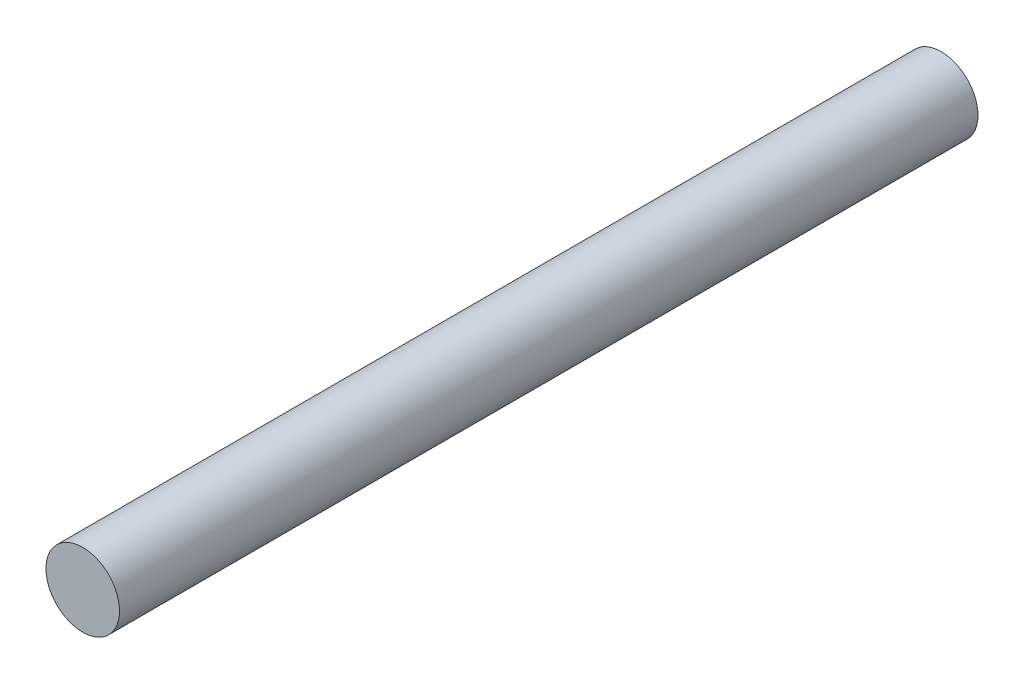
SolidWorks part; units mm, degrees
ref_plane "Front Plane" through (0, 0, 0) normal (0, 0, 1) x (1, 0, 0)
ref_plane "Top Plane" through (0, 0, 0) normal (0, 1, 0) x (1, 0, 0)
ref_plane "Right Plane" through (0, 0, 0) normal (1, 0, 0) x (0, 0, -1)
sketch "Sketch1" plane through (0, 0, 0) normal (0, 0, 1) x (1, 0, 0)
  circle A0 centre (0, 0) radius 3
  dimension "D1" = 6
extrude "Boss-Extrude1" add sketch "Sketch1" along normal mid plane 70
